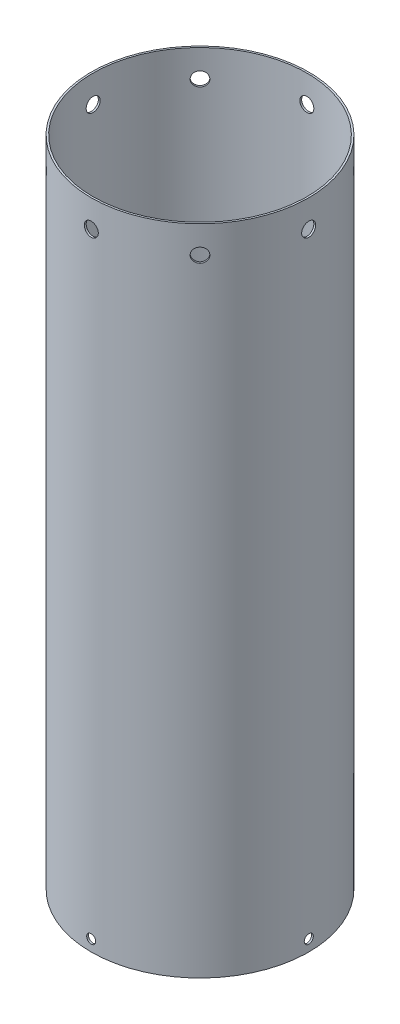
SolidWorks part; units mm, degrees
material "6061-T6 (SS)"
ref_plane "Front Plane" through (0, 0, 0) normal (0, 0, 1) x (1, 0, 0)
ref_plane "Top Plane" through (0, 0, 0) normal (0, 1, 0) x (1, 0, 0)
ref_plane "Right Plane" through (0, 0, 0) normal (1, 0, 0) x (0, 0, -1)
sketch "Sketch1" plane through (0, 0, 0) normal (0, 1, 0) x (1, 0, 0)
  circle A0 centre (0, 0) radius 76.2
  dimension "D1" = 152.4
extrude "Boss-Extrude1" add sketch "Sketch1" along normal blind 457.2
sketch "Sketch2" plane through (0, 457.2, 0) normal (0, 1, 0) x (1, 0, 0)
  circle A0 centre (0, 0) radius 74.93
  dimension "D1" = 149.86
extrude "Cut-Extrude1" cut sketch "Sketch2" against normal through all
sketch "Sketch3" plane through (0, 0, 0) normal (0, 0, 1) x (1, 0, 0)
  line L0 (0, 457.2) -> (0, 438.15)
  line L1 (76.2, 457.2) -> (-76.2, 457.2) construction
  circle A0 centre (0, 438.15) radius 4.8895
  dimension "D1" = 19.05
  dimension "D2" = 9.779
extrude "Cut-Extrude2" cut sketch "Sketch3" against normal through all both and the other way through all contours A0
pattern_circular "CirPattern1" count 8 over 360 about axis through (0, 457.2, 0) along (0, -1, 0) of "Cut-Extrude2"
sketch "Sketch4" plane through (0, 0, 0) normal (0, 0, 1) x (1, 0, 0)
  line L0 (0, 0) -> (0, 7.9375)
  line L1 (-76.2, 0) -> (76.2, 0) construction
  circle A0 centre (0, 7.9375) radius 3.175
extrude "Cut-Extrude3" cut sketch "Sketch4" against normal through all both and the other way through all contours A0
pattern_circular "CirPattern2" count 4 over 360 about axis through (0, 457.2, 0) along (0, -1, 0) of "Cut-Extrude3"
